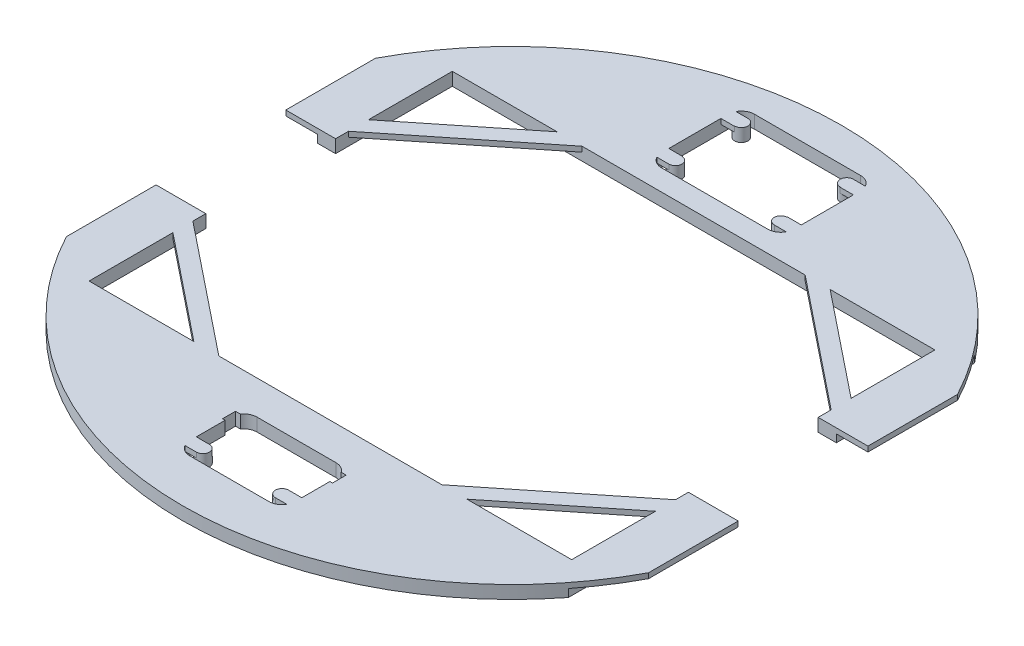
SolidWorks part; units mm, degrees
ref_plane "Front Plane" through (0, 0, 0) normal (0, 0, 1) x (1, 0, 0)
ref_plane "Top Plane" through (0, 0, 0) normal (0, 1, 0) x (1, 0, 0)
ref_plane "Right Plane" through (0, 0, 0) normal (1, 0, 0) x (0, 0, -1)
sketch "Sketch1" plane through (0, 0, 0) normal (0, 1, 0) x (1, 0, 0)
  circle A0 centre (0, 0) radius 63.5
  dimension "D1" = 127
extrude "Boss-Extrude1" add sketch "Sketch1" along normal blind 2.5
sketch "Sketch2" plane through (0, 0, 0) normal (0, 1, 0) x (1, 0, 0)
  line L1 (-46.5, 35) -> (46.5, 35)
  line L2 (-46.5, 35) -> (-46.5, -35)
  line L3 (-46.5, -35) -> (46.5, -35)
  line L4 (46.5, 35) -> (46.5, -35)
  line L5 (-46.5, 35) -> (46.5, -35) construction
  line L6 (-46.5, -35) -> (46.5, 35) construction
  point P0 (0, 0)
  dimension "D1" = 70
  dimension "D2" = 93
sketch "Sketch4" plane through (0, 2.5, 0) normal (0, 1, 0) x (1, 0, 0)
  line L0 (-46.5, 15) -> (-21.5, 35)
  line L1 (-46.5, 35) -> (-26.3023, 35)
  line L2 (-46.5, 35) -> (-46.5, 18.8419)
  line L3 (-46.5, -35) -> (-26.3023, -35)
  line L4 (46.5, 35) -> (46.5, 18.8419)
  line L5 (-46.5, 35) -> (46.5, -35) construction
  line L6 (-46.5, -35) -> (46.5, 35) construction
  line L7 (-46.5, 18.8419) -> (-26.3023, 35)
  line L8 (0, 35) -> (0, -35) construction
  line L9 (-46.5, 0) -> (46.5, 0) construction
  line L10 (-48.3741, 17.3426) -> (-23.3741, 37.3426) construction
  line L11 (46.5, 15) -> (21.5, 35)
  line L12 (46.5, 18.8419) -> (26.3023, 35)
  line L13 (-46.5, -18.8419) -> (-26.3023, -35)
  line L14 (-46.5, -15) -> (-21.5, -35)
  line L15 (46.5, -15) -> (21.5, -35)
  line L16 (46.5, -18.8419) -> (26.3023, -35)
  line L17 (-21.5, 35) -> (21.5, 35)
  line L18 (-46.5, 15) -> (-46.5, -15)
  line L19 (26.3023, 35) -> (46.5, 35)
  line L20 (46.5, 15) -> (46.5, -15)
  line L21 (46.5, -18.8419) -> (46.5, -35)
  line L22 (26.3023, -35) -> (46.5, -35)
  line L23 (-21.5, -35) -> (21.5, -35)
  line L24 (-46.5, -18.8419) -> (-46.5, -35)
  point P0 (0, 0)
  dimension "D1" = 25
  dimension "D2" = 20
  dimension "D3" = 3
extrude "Cut-Extrude3" cut sketch "Sketch4" against normal blind 10
extrude "Cut-Extrude4" cut sketch "Sketch2" along normal blind 1.5
sketch "Sketch5" plane through (0, 2.5, 0) normal (0, 1, 0) x (1, 0, 0)
  line L1 (-46.5, 0) -> (46.5, 0) construction
  line L2 (-46.5, 15) -> (-46.5, -15) construction
  line L3 (46.5, -15) -> (46.5, 15) construction
  line L14 (-56.0892, 12.5) -> (-46.5, 12.5)
  line L15 (-56.0892, 12.5) -> (-56.0892, 29.77)
  line L17 (56.0892, 12.5) -> (56.0892, 29.77) construction
  line L18 (-56.0892, 12.5) -> (56.0892, 29.77) construction
  line L19 (-56.0892, 29.77) -> (56.0892, 12.5) construction
  line L20 (56.0892, -12.5) -> (56.0892, -29.77) construction
  line L21 (-56.0892, -12.5) -> (-46.5, -12.5)
  line L22 (-56.0892, -12.5) -> (-56.0892, -29.77)
  line L23 (-46.5, -12.5) -> (-46.5, 12.5)
  line L24 (46.5, 12.5) -> (46.5, -12.5) construction
  line L25 (46.5, -12.5) -> (56.0892, -12.5) construction
  line L26 (46.5, 12.5) -> (56.0892, 12.5) construction
  line L27 (0, 35) -> (0, -35) construction
  line L28 (21.5, 35) -> (-21.5, 35) construction
  line L29 (-21.5, -35) -> (21.5, -35) construction
  line L30 (56.0892, 12.5) -> (56.0892, 29.77)
  line L31 (56.0892, -12.5) -> (56.0892, -29.77)
  line L32 (56.0892, -12.5) -> (46.5, -12.5)
  line L33 (46.5, -12.5) -> (46.5, 12.5)
  line L34 (56.0892, 12.5) -> (46.5, 12.5)
  arc A0 (-56.0892, -29.77) -> (-56.0892, 29.77) centre (0, 0) cw
  circle A1 centre (0, 0) radius 63.5 construction
  arc A3 (56.0892, -29.77) -> (56.0892, 29.77) centre (0, 0) ccw construction
  arc A4 (56.0892, 29.77) -> (56.0892, -29.77) centre (0, 0) cw construction
  arc A5 (56.0892, -29.77) -> (56.0892, 29.77) centre (0, 0) ccw
  point P0 (0, 21.135)
  dimension "D1" = 113.5
  dimension "D2" = 25
extrude "Cut-Extrude5" cut sketch "Sketch5" against normal blind 10
sketch "Sketch6" plane through (0, 0, 0) normal (0, -1, 0) x (1, 0, 0)
  line L0 (0, -35) -> (0, 35) construction
  line L5 (46.5, -35) -> (-46.5, -35) construction
  line L6 (-46.5, 35) -> (46.5, 35) construction
  line L7 (69.548, 0) -> (-69.548, 0) construction
  line L14 (60, -39.4506) -> (50, -39.4506)
  line L15 (-60, -12.5) -> (-50, -12.5)
  line L16 (-60, -12.5) -> (-60, -39.4506)
  line L17 (-60, -39.4506) -> (-50, -39.4506)
  line L18 (-50, -12.5) -> (-50, -39.4506)
  line L19 (50, -12.5) -> (50, -39.4506)
  line L20 (60, -12.5) -> (50, -12.5)
  line L21 (60, -12.5) -> (60, -39.4506)
  line L22 (-60, 39.4506) -> (-50, 39.4506)
  line L23 (-50, 12.5) -> (-50, 39.4506)
  line L24 (-60, 12.5) -> (-50, 12.5)
  line L25 (-60, 12.5) -> (-60, 39.4506)
  line L26 (60, 12.5) -> (60, 39.4506)
  line L27 (60, 12.5) -> (50, 12.5)
  line L28 (50, 12.5) -> (50, 39.4506)
  line L29 (60, 39.4506) -> (50, 39.4506)
  circle A0 centre (0, 0) radius 61.2883 construction
  point P15 (0, 0)
  dimension "D2" = 50
extrude "Cut-Extrude6" cut sketch "Sketch6" against normal blind 1.5
sketch "Sketch7" plane through (0, 2.5, 0) normal (0, 1, 0) x (1, 0, 0)
  line L0 (0, 56.9535) -> (0, 39.0465) construction
  line L1 (-10.2235, 56.9535) -> (10.2235, 56.9535)
  line L2 (-12.7635, 54.4135) -> (-12.7635, 41.5865)
  line L3 (-10.2235, 39.0465) -> (10.2235, 39.0465)
  line L4 (12.7635, 54.4135) -> (12.7635, 41.5865)
  line L5 (-12.7635, 56.9535) -> (12.7635, 39.0465) construction
  line L6 (-12.7635, 39.0465) -> (12.7635, 56.9535) construction
  line L7 (-7.62, -41.523) -> (7.62, -41.523)
  line L8 (-10.16, -45.123) -> (-10.16, -51.937)
  line L9 (-7.62, -54.477) -> (7.62, -54.477)
  line L10 (10.16, -45.25) -> (10.16, -51.937)
  line L11 (-10.16, -41.523) -> (10.16, -54.477) construction
  line L12 (-10.16, -54.477) -> (10.16, -41.523) construction
  line L13 (-10.16, 54.35) -> (10.16, 54.35) construction
  line L14 (-7.62, -44.063) -> (7.62, -44.063) construction
  line L15 (-7.62, -44.063) -> (-7.62, -51.937) construction
  line L16 (-7.62, -51.937) -> (7.62, -51.937) construction
  line L17 (7.62, -44.063) -> (7.62, -51.937) construction
  line L18 (-7.62, -44.063) -> (7.62, -51.937) construction
  line L19 (-7.62, -51.937) -> (7.62, -44.063) construction
  line L20 (-10.16, 54.35) -> (-10.16, 41.65) construction
  line L21 (-10.16, 41.65) -> (10.16, 41.65) construction
  line L22 (10.16, 54.35) -> (10.16, 41.65) construction
  line L23 (-10.16, 54.35) -> (10.16, 41.65) construction
  line L24 (-10.16, 41.65) -> (10.16, 54.35) construction
  line L25 (-12.7635, 48) -> (12.7635, 48) construction
  line L26 (9.7124, -42.623) -> (10.66, -42.623)
  line L27 (-10.66, -42.623) -> (-9.7124, -42.623)
  line L28 (-10.66, -42.623) -> (-10.66, -45.123)
  line L29 (-10.66, -45.123) -> (-10.16, -45.123)
  line L30 (10.66, -42.623) -> (10.66, -45.25)
  line L31 (10.16, -45.25) -> (10.66, -45.25)
  arc A0 (-12.7635, 41.5865) -> (-10.2235, 39.0465) centre (-10.2235, 41.5865) ccw
  arc A1 (10.2235, 39.0465) -> (12.7635, 41.5865) centre (10.2235, 41.5865) ccw
  arc A2 (10.2235, 56.9535) -> (12.7635, 54.4135) centre (10.2235, 54.4135) cw
  arc A3 (-10.2235, 56.9535) -> (-12.7635, 54.4135) centre (-10.2235, 54.4135) ccw
  arc A4 (-10.16, -51.937) -> (-7.62, -54.477) centre (-7.62, -51.937) ccw
  arc A5 (7.62, -54.477) -> (10.16, -51.937) centre (7.62, -51.937) ccw
  arc A6 (7.62, -41.523) -> (9.7124, -42.623) centre (7.62, -44.063) cw
  arc A7 (-7.62, -41.523) -> (-9.7124, -42.623) centre (-7.62, -44.063) ccw
  circle A10 centre (10.16, 54.35) radius 1.27
  circle A11 centre (-10.16, 54.35) radius 1.27
  circle A12 centre (10.16, 41.65) radius 1.27
  circle A13 centre (-10.16, 41.65) radius 1.27
  circle A14 centre (-7.62, -51.937) radius 1.27
  circle A15 centre (7.62, -51.937) radius 1.27
  point P0 (0, 48)
  point P5 (0, -48)
  point P36 (0, -48)
  point P42 (0, 48)
  dimension "D7" = 2.54
  dimension "D8" = 2.54
  dimension "D11" = 0.5
  dimension "D12" = 0.5
  dimension "D15" = 2.54
  dimension "D16" = 2.54
  dimension "D17" = 2.54
  dimension "D1" = 17.907
  dimension "D2" = 25.527
  dimension "D3" = 48
  dimension "D4" = 12.954
  dimension "D5" = 20.32
  dimension "D6" = 48
  dimension "D9" = 15.24
  dimension "D10" = 2.54
  dimension "D13" = 12.7
  dimension "D14" = 20.32
  dimension "D18" = 1.1
  dimension "D19" = 2.5
extrude "Cut-Extrude7" cut sketch "Sketch7" against normal through all
sketch "Sketch8" plane through (0, 2.5, 0) normal (0, 1, 0) x (1, 0, 0)
  line L0 (12.7635, 41.5865) -> (12.7635, 54.4135) construction
  line L1 (10.16, 55.62) -> (12.7635, 55.62)
  line L2 (10.16, 55.62) -> (10.16, 53.0165)
  line L3 (10.16, 53.0165) -> (12.7635, 53.0165)
  line L4 (12.7635, 55.62) -> (12.7635, 53.0165)
  line L5 (-12.7635, 54.4135) -> (-12.7635, 41.5865) construction
  line L6 (-10.16, 55.62) -> (-12.7635, 55.62)
  line L7 (-10.16, 55.62) -> (-10.16, 53.0165)
  line L8 (-10.16, 53.0165) -> (-12.7635, 53.0165)
  line L9 (-12.7635, 55.62) -> (-12.7635, 53.0165)
  line L10 (-10.16, -45.123) -> (-10.16, -51.937) construction
  line L11 (-10.16, 40.38) -> (-12.7635, 40.38)
  line L12 (-10.16, 40.38) -> (-10.16, 42.9835)
  line L13 (-10.16, 42.9835) -> (-12.7635, 42.9835)
  line L14 (-12.7635, 40.38) -> (-12.7635, 42.9835)
  line L15 (10.16, 40.38) -> (12.7635, 40.38)
  line L16 (10.16, 40.38) -> (10.16, 42.9835)
  line L17 (10.16, 42.9835) -> (12.7635, 42.9835)
  line L18 (12.7635, 40.38) -> (12.7635, 42.9835)
  line L19 (-7.62, -53.207) -> (-10.16, -53.207)
  line L20 (-7.62, -53.207) -> (-7.62, -50.667)
  line L21 (-7.62, -50.667) -> (-10.16, -50.667)
  line L22 (-10.16, -53.207) -> (-10.16, -50.667)
  line L23 (10.16, -51.937) -> (10.16, -45.25) construction
  line L24 (7.62, -53.207) -> (10.16, -53.207)
  line L25 (7.62, -53.207) -> (7.62, -50.667)
  line L26 (7.62, -50.667) -> (10.16, -50.667)
  line L27 (10.16, -53.207) -> (10.16, -50.667)
  circle A0 centre (10.16, 54.35) radius 1.27 construction
  circle A1 centre (-10.16, 54.35) radius 1.27 construction
  circle A2 centre (-10.16, 41.65) radius 1.27 construction
  circle A3 centre (10.16, 41.65) radius 1.27 construction
  circle A4 centre (-7.62, -51.937) radius 1.27 construction
  circle A5 centre (7.62, -51.937) radius 1.27 construction
extrude "Boss-Extrude4" add sketch "Sketch8" against normal blind 1
